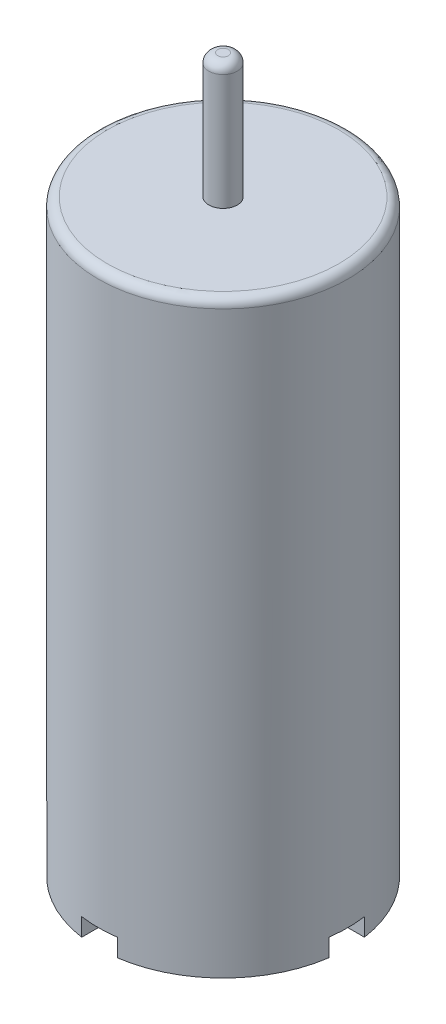
SolidWorks part; units mm, degrees
material "1060 Alloy"
ref_plane "Front Plane" through (0, 0, 0) normal (0, 0, 1) x (1, 0, 0)
ref_plane "Top Plane" through (0, 0, 0) normal (0, 1, 0) x (1, 0, 0)
ref_plane "Right Plane" through (0, 0, 0) normal (1, 0, 0) x (0, 0, -1)
sketch "Sketch1" plane through (0, 0, 0) normal (0, 1, 0) x (1, 0, 0)
  circle A0 centre (0, 0) radius 3.5
  dimension "D1" = 7
extrude "Boss-Extrude1" add sketch "Sketch1" along normal blind 16
sketch "Sketch2" plane through (0, 0, 0) normal (0, -1, 0) x (1, 0, 0)
  line L0 (0, 3.5) -> (0, -3.5) construction
  line L1 (-3.5, 0) -> (3.5, 0) construction
  line L2 (-0.5, 2.9641) -> (0.5, 2.9641)
  line L3 (-0.5, 2.9641) -> (-0.5, 3.4641)
  line L4 (0.5, 2.9641) -> (0.5, 3.4641)
  line L5 (2.9641, 0.5) -> (3.4641, 0.5)
  line L6 (2.9641, 0.5) -> (2.9641, -0.5)
  line L7 (2.9641, -0.5) -> (3.4641, -0.5)
  line L8 (0.5, -2.9641) -> (0.5, -3.4641)
  line L9 (0.5, -2.9641) -> (-0.5, -2.9641)
  line L10 (-0.5, -2.9641) -> (-0.5, -3.4641)
  line L11 (-2.9641, -0.5) -> (-3.4641, -0.5)
  line L12 (-2.9641, -0.5) -> (-2.9641, 0.5)
  line L13 (-2.9641, 0.5) -> (-3.4641, 0.5)
  arc A0 (-3.4641, -0.5) -> (-0.5, -3.4641) centre (0, 0) ccw
  circle A1 centre (0, 0) radius 3.5 construction
  arc A2 (3.4641, 0.5) -> (0.5, 3.4641) centre (0, 0) ccw
  arc A3 (0.5, -3.4641) -> (3.4641, -0.5) centre (0, 0) ccw
  arc A4 (-0.5, 3.4641) -> (-3.4641, 0.5) centre (0, 0) ccw
  point P11 (0, 2.9641)
  point P29 (0, 0)
  dimension "D1" = 1
  dimension "D2" = 0.5
  dimension "D3" = 4
extrude "Boss-Extrude2" add sketch "Sketch2" along normal blind 0.5
sketch "Sketch3" plane through (0, 16, 0) normal (0, 1, 0) x (1, 0, 0)
  circle A0 centre (0, 0) radius 0.4
  dimension "D1" = 0.8
extrude "Boss-Extrude3" add sketch "Sketch3" along normal blind 3.5
fillet "Fillet2" radius 0.25 1 edges at (0, 16, 3.5)
fillet "Fillet3" radius 0.25 1 edges at (0, 19.5, 0.4)
